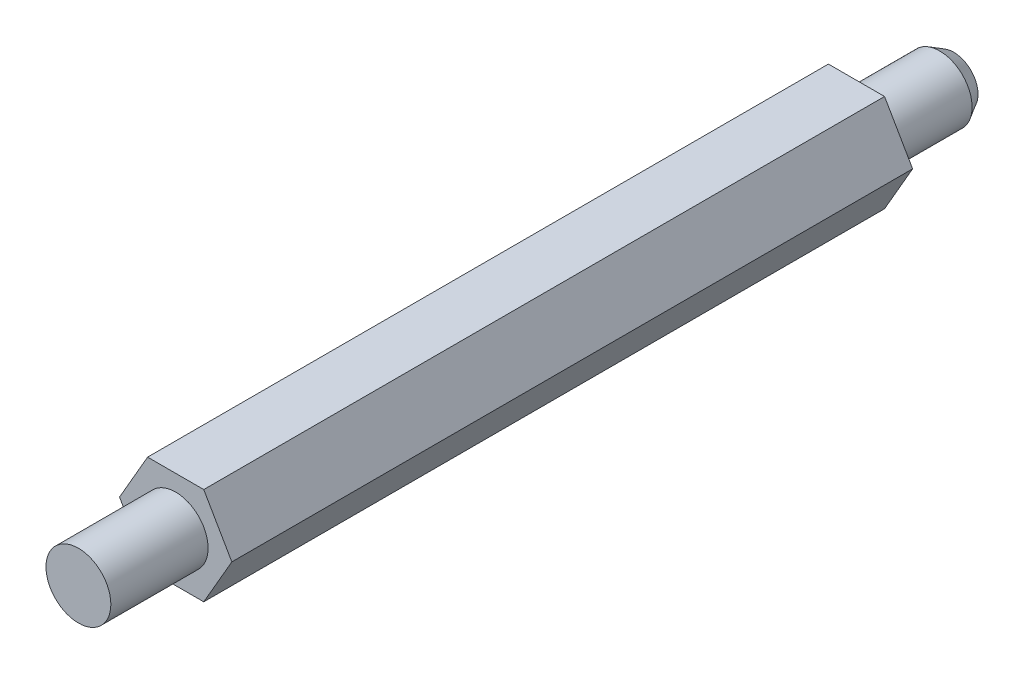
SolidWorks part; units mm, degrees
ref_plane "前视基准面" through (0, 0, 0) normal (0, 0, 1) x (1, 0, 0)
ref_plane "上视基准面" through (0, 0, 0) normal (0, 1, 0) x (1, 0, 0)
ref_plane "右视基准面" through (0, 0, 0) normal (1, 0, 0) x (0, 0, -1)
sketch "草图1" plane through (0, 0, 0) normal (0, 0, 1) x (1, 0, 0)
  line L0 (-28.6627, 0) -> (33.6774, 0) construction
  line L1 (1.7321, -3) -> (3.4641, 0)
  line L2 (3.4641, 0) -> (1.7321, 3)
  line L3 (1.7321, 3) -> (-1.7321, 3)
  line L4 (-1.7321, 3) -> (-3.4641, 0)
  line L5 (-3.4641, 0) -> (-1.7321, -3)
  line L6 (-1.7321, -3) -> (1.7321, -3)
  circle A0 centre (0, 0) radius 3 construction
  dimension "D1" = 6
extrude "拉伸1" add sketch "草图1" along normal blind 42
sketch "草图2" plane through (0, 0, 42) normal (0, 0, 1) x (1, 0, 0)
  circle A0 centre (0, 0) radius 2
  dimension "D1" = 4
extrude "拉伸2" add sketch "草图2" along normal blind 6 and the other way offset from surface (48 mm away) 6 other way up to face at (0, 0, 0)
chamfer "倒角1" distance 0.5 angle 60 1 edges at (-2, 0, -6)
